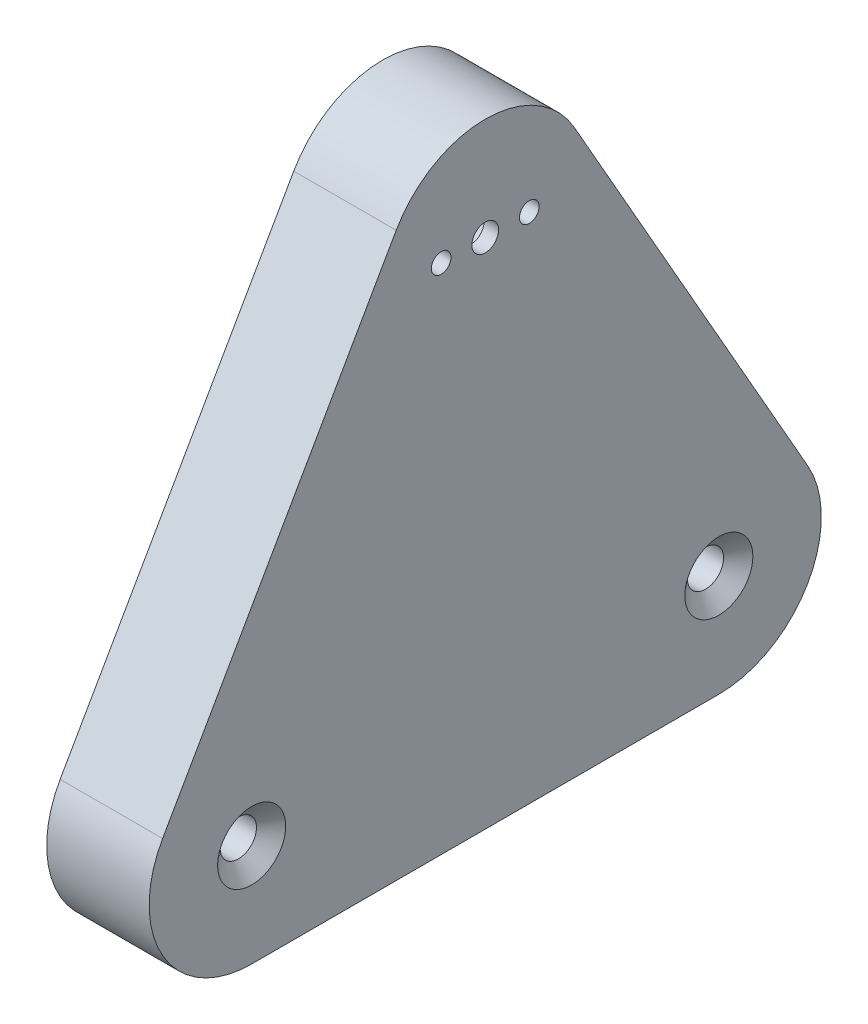
SolidWorks part; units mm, degrees
ref_plane "Front Plane" through (0, 0, 0) normal (0, 0, 1) x (1, 0, 0)
ref_plane "Top Plane" through (0, 0, 0) normal (0, 1, 0) x (1, 0, 0)
ref_plane "Right Plane" through (0, 0, 0) normal (1, 0, 0) x (0, 0, -1)
sketch "Sketch1" plane through (0, 0, 0) normal (0, 1, 0) x (1, 0, 0)
  circle A0 centre (0, 0) radius 12.7
  dimension "D1" = 25.4
extrude "Boss-Extrude1" add sketch "Sketch1" along normal blind 12.7
sketch "Sketch2" plane through (0, 0, 0) normal (0, -1, 0) x (1, 0, 0)
  circle A0 centre (0, 0) radius 1.6256
  dimension "D1" = 3.2512
extrude "Cut-Extrude1" cut sketch "Sketch2" against normal blind 9.525
sketch "Sketch3" plane through (0, 0, 0) normal (0, -1, 0) x (1, 0, 0)
  circle A0 centre (0, 0) radius 9.525
  dimension "D1" = 19.05
extrude "Cut-Extrude2" [suppressed] cut sketch "Sketch3" against normal blind 2.54 contours A0
sketch "Sketch14" plane through (0, 12.7, 0) normal (0, 1, 0) x (1, 0, 0)
  line L0 (0, 12.7) -> (15.875, 12.7)
  line L1 (15.875, 12.7) -> (15.875, -12.7)
  line L2 (15.875, -12.7) -> (0, -12.7)
  circle A0 centre (0, 0) radius 12.7
  circle M3 centre (0, 0) radius 12.7
  dimension "D1" = 25.4
  dimension "D2" = 15.875
extrude "Boss-Extrude6" add sketch "Sketch14" against normal up to surface (12.7 mm away) contours L2 L1 L0 M3 up to face at (0, 0, -1.6256)
hole_wizard "#2-56 Tapped Hole1" [suppressed] positions "Sketch6" profile "Sketch5" tap size "#2-56" standard "ANSI Inch"
sketch "Sketch6" [suppressed] plane through (0, 0, 0) normal (0, 0, 1) x (1, 0, 0)
  line L1 (-1.6256, 2.54) -> (1.6256, 2.54) construction
  point P0 (0, 3.81)
  dimension "D1" = 1.27
sketch "Sketch5" plane through (0, 3.81, 0) normal (1, 0, 0) x (0, 1, 0)
  line L0 (0, 0) -> (0, 13.7422)
  line L1 (0, 13.7422) -> (0.889, 13.208)
  line L2 (0.889, 13.208) -> (0.889, 0)
  line L5 (0.889, 0) -> (0, 0)
  line L10 (0, 13.7422) -> (-0.889, 13.208) construction
  line L11 (0, -6.35) -> (0, 107.95) construction
  dimension "Tap Drill Dia." = 1.778
  dimension "Tap Drill Depth" = 13.208
  dimension "Drill Angle" = 118
sketch "Sketch15" plane through (15.875, 0, 0) normal (1, 0, 0) x (0, 0, -1)
  line L1 (12.7, 12.7) -> (-12.7, 12.7) construction
  line L2 (-12.7, 25.4) -> (-12.7, 12.7)
  line L3 (-12.7, 12.7) -> (12.7, 12.7)
  line L4 (12.7, 12.7) -> (12.7, 25.4)
  circle A0 centre (0, 25.4) radius 12.7
  line M4 (12.7, 12.7) -> (-12.7, 12.7)
  dimension "D1" = 25.4
  dimension "D2" = 12.7
  dimension "D3" = 0
extrude "Boss-Extrude8" add sketch "Sketch15" against normal blind 12.7 contours A0 | A0 L2 L3 | A0 L4 M4
sketch "Sketch17" plane through (3.175, 0, 0) normal (-1, 0, 0) x (0, 0, 1)
  line L0 (-12.7, 25.4) -> (12.7, 25.4) construction
  line L1 (0, 38.1) -> (0, 12.7) construction
  line L2 (-12.7, 12.7) -> (12.7, 12.7) construction
  arc A0 (12.7, 25.4) -> (-12.7, 25.4) centre (0, 25.4) ccw construction
  circle A1 centre (0, 25.4) radius 1.651
  dimension "D1" = 3.302
extrude "Cut-Extrude4" cut sketch "Sketch17" against normal up to surface (12.7 mm away) up to face at (15.875, 15.875, 0)
sketch "Sketch18" plane through (3.175, 0, 0) normal (-1, 0, 0) x (0, 0, 1)
  circle A0 centre (0, 25.4) radius 3.81
  dimension "D1" = 7.62
extrude "Cut-Extrude5" cut sketch "Sketch18" against normal offset from surface (10.9028 mm away) 1.7972 up to face at (15.875, 25.4, 1.651)
sketch "Sketch19" plane through (3.175, 0, 0) normal (-1, 0, 0) x (0, 0, 1)
  circle A0 centre (0, 25.4) radius 8.255
  dimension "D1" = 16.51
extrude "Cut-Extrude6" cut sketch "Sketch19" against normal offset from surface (8.3628 mm away) 4.3372 up to face at (15.875, 25.4, 1.651)
sketch "Sketch20" plane through (3.175, 0, 0) normal (-1, 0, 0) x (0, 0, 1)
  circle A0 centre (0, 25.4) radius 9.525
  dimension "D1" = 19.05
extrude "Cut-Extrude7" cut sketch "Sketch20" against normal offset from surface (5.1878 mm away) 7.5122 up to face at (15.875, 25.4, 1.651)
sketch "Sketch21" plane through (11.5378, 0, 0) normal (-1, 0, 0) x (0, 0, 1)
  line L0 (8.255, 25.4) -> (-8.255, 25.4) construction
  circle A0 centre (0, 25.4) radius 8.255 construction
  circle A1 centre (5.46, 25.4) radius 1.2192
  circle A2 centre (-5.46, 25.4) radius 1.2192
  circle A3 centre (0, 25.4) radius 1.651 construction
  dimension "D1" = 2.4384
  dimension "D2" = 2.4384
  dimension "D3" = 10.92
  dimension "D4" = 5.46
extrude "Cut-Extrude8" cut sketch "Sketch21" against normal up to surface (4.3372 mm away) up to face at (15.875, 25.4, 1.651)
sketch "Sketch22" plane through (0, 12.7, 0) normal (0, 1, 0) x (1, 0, 0)
  line L1 (3.175, -12.7) -> (-12.7, -12.7)
  line L2 (3.175, -12.7) -> (3.175, 12.7)
  line L3 (3.175, 12.7) -> (-12.7, 12.7)
  line L4 (-12.7, -12.7) -> (-12.7, 12.7)
  arc A0 (0, 12.7) -> (0, -12.7) centre (0, 0) ccw construction
extrude "Cut-Extrude9" cut sketch "Sketch22" against normal through all
sketch "Sketch23" plane through (0, 0, 0) normal (0, -1, 0) x (1, 0, 0)
  line L1 (3.175, 12.7) -> (15.875, 12.7)
  line L2 (3.175, 12.7) -> (3.175, -12.7)
  line L3 (3.175, -12.7) -> (15.875, -12.7)
  line L4 (15.875, 12.7) -> (15.875, -12.7)
extrude "Boss-Extrude9" add sketch "Sketch23" along normal blind 38.1
sketch "Sketch24" plane through (3.175, 0, 0) normal (-1, 0, 0) x (0, 0, 1)
  line L0 (12.7, 25.4) -> (12.7, -38.1) construction
  line L1 (12.7, 6.35) -> (-12.7, 6.35)
  line L2 (12.7, 6.35) -> (12.7, -12.7)
  line L3 (12.7, -12.7) -> (-12.7, -12.7)
  line L4 (-12.7, 6.35) -> (-12.7, -12.7)
  line L5 (-12.7, -38.1) -> (-12.7, 25.4) construction
  circle A0 centre (0, 25.4) radius 9.525 construction
  dimension "D1" = 19.05
  dimension "D2" = 19.05
extrude "Boss-Extrude10" [suppressed] add sketch "Sketch24" along normal blind 28.575
sketch "Sketch26" [suppressed] plane through (-25.4, 0, 0) normal (-1, 0, 0) x (0, 0, 1)
  line L1 (-12.7, 6.35) -> (12.7, 6.35)
  line L2 (-12.7, 6.35) -> (-12.7, -50.8)
  line L3 (-12.7, -50.8) -> (12.7, -50.8)
  line L4 (12.7, 6.35) -> (12.7, -50.8)
extrude "Boss-Extrude11" [suppressed] add sketch "Sketch26" along normal blind 12.7 contours L2 L3 L4 L1
sketch "Sketch28" plane through (15.875, 0, 0) normal (1, 0, 0) x (0, 0, -1)
  line L0 (-11.0344, 31.6875) -> (-50.8, -38.1)
  line L1 (-50.8, -38.1) -> (50.8, -38.1)
  line L2 (50.8, -38.1) -> (11.0344, 31.6875)
  line L3 (-11.0344, 31.6875) -> (-11.0344, -38.1)
  line L4 (12.7, -38.1) -> (-12.7, -38.1) construction
  line L5 (0, 38.1) -> (0, -38.1) construction
  line L6 (11.0344, 31.6875) -> (11.0344, -38.1)
  arc A0 (12.7, 25.4) -> (-12.7, 25.4) centre (0, 25.4) ccw construction
  line M4 (-12.7, 25.4) -> (-12.7, -38.1)
  line M6 (12.7, -38.1) -> (12.7, 25.4)
  arc M7 (12.7, 25.4) -> (-12.7, 25.4) centre (0, 25.4) ccw
  dimension "D1" = 101.6
  dimension "D2" = 50.8
extrude "Boss-Extrude13" add sketch "Sketch28" against normal up to surface (12.7 mm away) contours L0 L1 M4 M7 | L1 L2 M7 M6 up to face at (3.175, 25.4, 9.525)
fillet "Fillet1" radius 12.7 2 edges at (9.525, -38.1, 50.8) (9.525, -38.1, -50.8)
hole_wizard "CSK for #8 Flat Head Machine Screw (100)1" positions "Sketch30" profile "Sketch31" countersink size "#8" standard "ANSI Inch" end condition through all
sketch "Sketch30" plane through (15.875, 0, 0) normal (1, 0, 0) x (0, 0, -1)
  point P2 (28.9464, -25.4)
  point P5 (-28.9464, -25.4)
sketch "Sketch31" plane through (15.875, -25.4, -28.9464) normal (0, 1, 0) x (0, 0, -1)
  line L0 (0, 0) -> (0, 12.7)
  line L1 (0, 12.7) -> (2.2479, 12.7)
  line L2 (2.2479, 12.7) -> (2.2479, 1.6518)
  line L3 (2.2479, 1.6518) -> (4.2164, 0)
  line L5 (4.2164, 0) -> (0, 0)
  line L6 (-2.2479, 1.6518) -> (-4.2164, 0) construction
  line L11 (0, -6.35) -> (0, 107.95) construction
  dimension "Thru Hole Dia." = 4.4958
  dimension "Thru Hole Depth" = 12.7
  dimension "Near C'Sink Dia." = 8.4328
  dimension "Near C'Sink Angle" = 100
